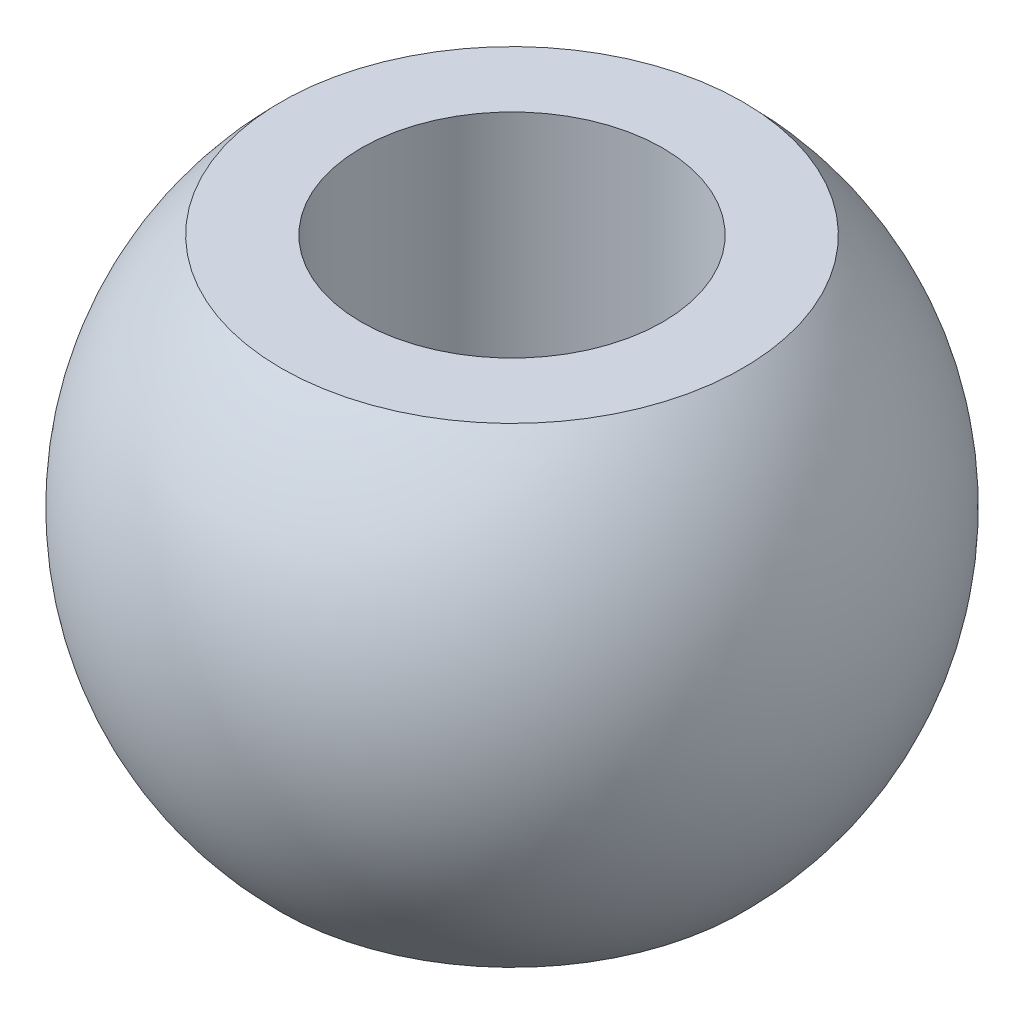
SolidWorks part; units mm, degrees
ref_plane "Front Plane" through (0, 0, 0) normal (0, 0, 1) x (1, 0, 0)
ref_plane "Top Plane" through (0, 0, 0) normal (0, 1, 0) x (1, 0, 0)
ref_plane "Right Plane" through (0, 0, 0) normal (1, 0, 0) x (0, 0, -1)
sketch "Sketch1" plane through (0, 0, 0) normal (1, 0, 0) x (0, 0, -1)
  line L0 (0, 2.5) -> (0, -2.5)
  line L1 (0, 2.5) -> (2.4495, 2.5)
  line L2 (0, -2.5) -> (2.4495, -2.5)
  arc A0 (2.4495, -2.5) -> (2.4495, 2.5) centre (0, 0) ccw
  dimension "D1" = 7
  dimension "D2" = 5
revolve "Revolve1" add sketch "Sketch1" angle 360 about L0
hole_wizard "M3 Clearance Hole1" positions "3DSketch1" profile "Sketch3" hole size "M3" standard "ANSI Metric"
sketch3d "3DSketch1"
  point P0 (0, 3.5, 0)
sketch "Sketch3" plane through (0, 3.5, 0) normal (1, 0, 0) x (0, 0, 1)
  line L0 (0, 0) -> (0, 8.4614)
  line L1 (0, 8.4614) -> (1.6, 7.5)
  line L2 (1.6, 7.5) -> (1.6, 0)
  line L5 (1.6, 0) -> (0, 0)
  line L10 (0, 8.4614) -> (-1.6, 7.5) construction
  line L11 (0, -6.35) -> (0, 107.95) construction
  dimension "Hole Dia." = 3.2
  dimension "Hole Depth" = 7.5
  dimension "Drill Angle" = 118
